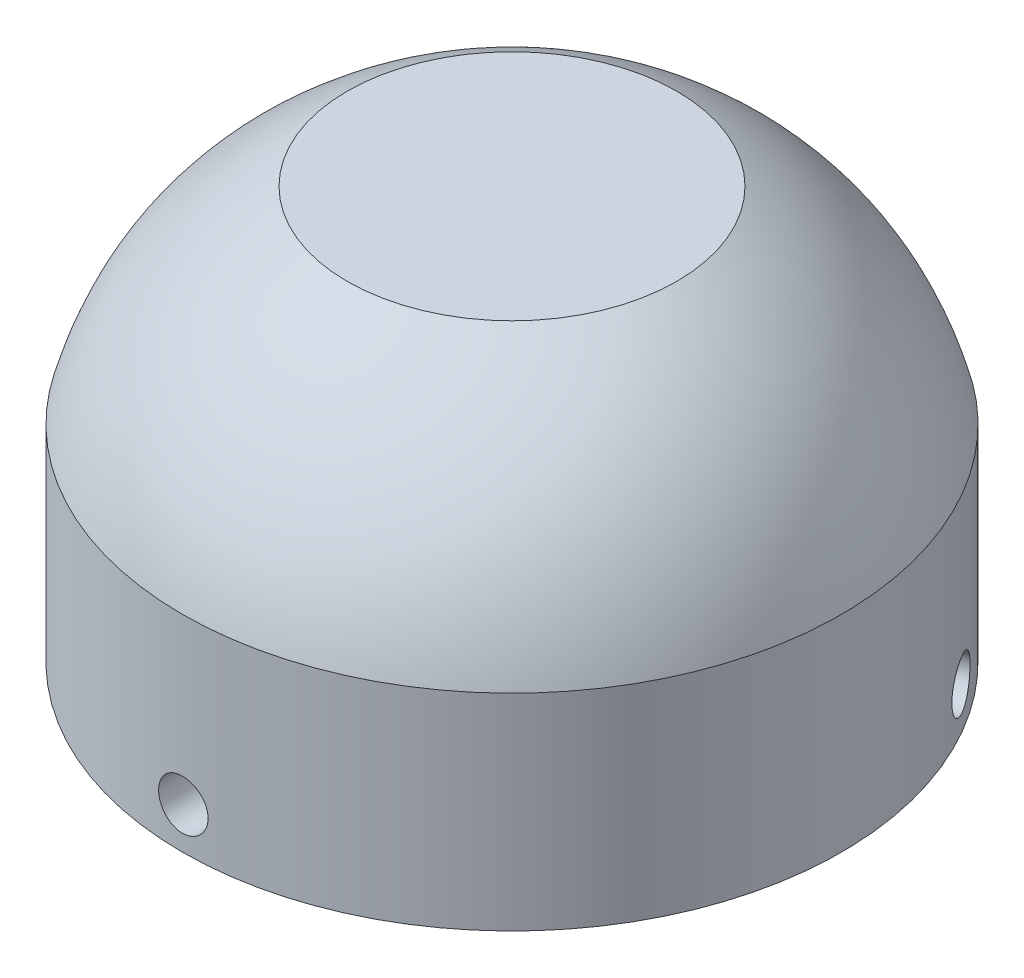
SolidWorks part; units mm, degrees
ref_plane "Front Plane" through (0, 0, 0) normal (0, 0, 1) x (1, 0, 0)
ref_plane "Top Plane" through (0, 0, 0) normal (0, 1, 0) x (1, 0, 0)
ref_plane "Right Plane" through (0, 0, 0) normal (1, 0, 0) x (0, 0, -1)
sketch "Sketch1" plane through (0, 0, 0) normal (0, 0, 1) x (1, 0, 0)
  line L0 (15.999, 0) -> (20.999, 0) construction
  line L1 (0, -63.9535) -> (0, 73.7209) construction
  line L2 (-20, 30) -> (0, 30)
  line L3 (0, 30) -> (0, 22.9289)
  line L4 (0, 22.9289) -> (-20, 22.9289)
  line L5 (-35, 0) -> (-40, 0) construction
  line L6 (-40, 0) -> (-40, 5)
  line L7 (-35, 0) -> (-35, -20)
  line L8 (-35, -20) -> (-40, -20)
  line L9 (-40, -20) -> (-40, 0)
  line L10 (-20, 30) -> (-20, 22.9289) construction
  line L11 (-35, 0) -> (-40, 5) construction
  line L12 (-40, 5) -> (-32.1, 9.7538) construction
  line L13 (-32.1, 9.7538) -> (-32.1, 20.5) construction
  spline S0 degree 2 poles (-20, 30) (-35.4489, 21.9814) (-40, 5) knots 0 0 0 1 1 1
  spline S1 degree 2 poles (-20, 22.9289) (-32.9925, 14.5797) (-35, 0) knots 0 0 0 1 1 1
  dimension "D1" = 20
  dimension "D2" = 30
  dimension "D3" = 5
  dimension "D4" = 15.5
  dimension "D5" = 7.9
  dimension "D6" = 40
  dimension "D7" = 5
  dimension "D8" = 9.22
  dimension "D9" = 20
revolve "Revolve1" add sketch "Sketch1" angle 360 about L1
ref_plane "Plane1" through (0, 0, 40) normal (0, 0, 1) x (1, 0, 0)
sketch "Sketch2" plane through (0, 0, 40) normal (0, 0, 1) x (1, 0, 0)
  line L0 (0, -27.9441) -> (0, 37.3854) construction
  line L1 (-40, -20) -> (40, -20) construction
  line L2 (-40, -20) -> (40, -20) construction
  circle A0 centre (0, -15) radius 3
  dimension "D2" = 6
  dimension "D1" = 5
extrude "Cut-Extrude1" cut sketch "Sketch2" against normal up to next
pattern_circular "CirPattern1" count 3 over 360 about axis through (0, 5, 0) along (0, -1, 0) of "Cut-Extrude1"
